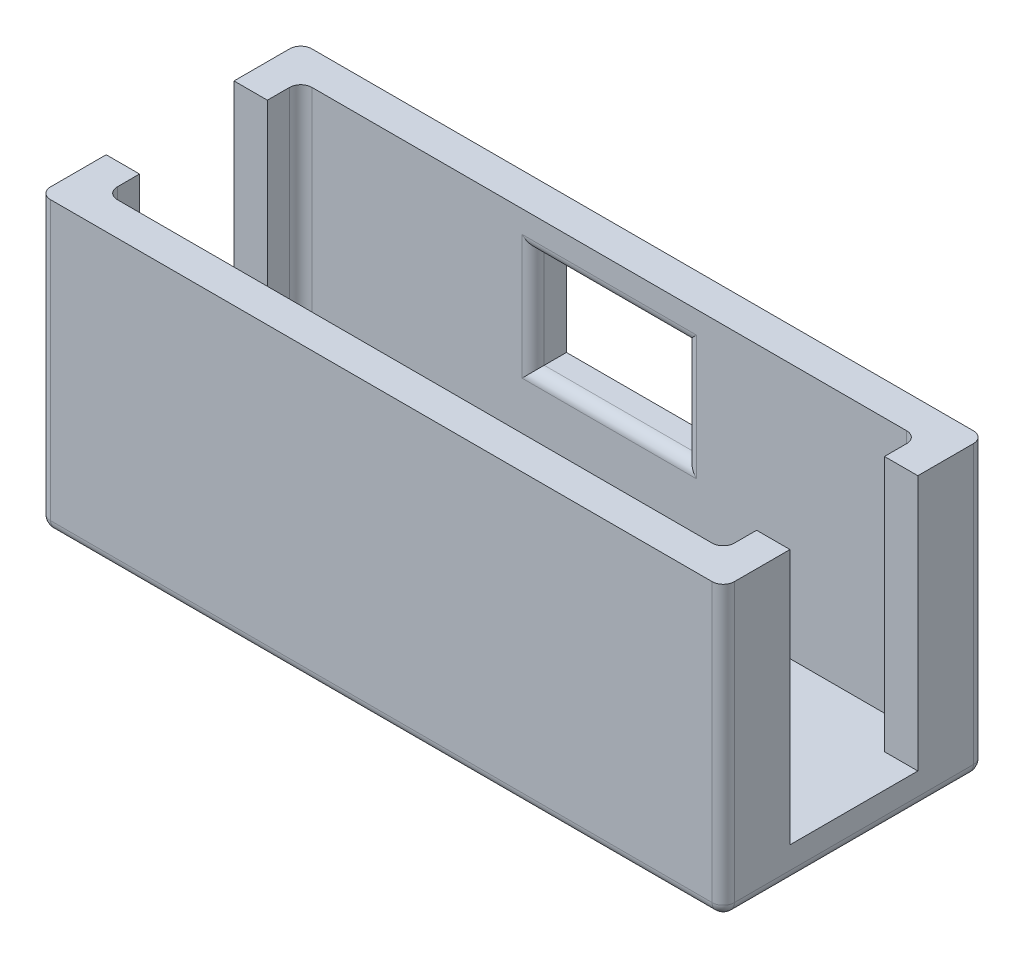
SolidWorks part; units mm, degrees
ref_plane "Front Plane" through (0, 0, 0) normal (0, 0, 1) x (1, 0, 0)
ref_plane "Top Plane" through (0, 0, 0) normal (0, 1, 0) x (1, 0, 0)
ref_plane "Right Plane" through (0, 0, 0) normal (1, 0, 0) x (0, 0, -1)
sketch "Sketch1" plane through (0, 0, 0) normal (0, 1, 0) x (1, 0, 0)
  line L0 (-33.75, -14.75) -> (-33.75, 14.75)
  line L1 (-30.75, -11.75) -> (30.75, -11.75)
  line L2 (-30.75, -11.75) -> (-30.75, 11.75)
  line L3 (-30.75, 11.75) -> (30.75, 11.75)
  line L4 (30.75, -11.75) -> (30.75, 11.75)
  line L5 (-30.75, -11.75) -> (30.75, 11.75) construction
  line L6 (-30.75, 11.75) -> (30.75, -11.75) construction
  line L7 (-33.75, 14.75) -> (33.75, 14.75)
  line L8 (33.75, -14.75) -> (33.75, 14.75)
  line L9 (-33.75, -14.75) -> (33.75, -14.75)
  point P0 (0, 0)
  dimension "D1" = 61.5
  dimension "D2" = 23.5
  dimension "D3" = 3
extrude "Boss-Extrude1" add sketch "Sketch1" along normal blind 3 contours L2 L1 L4 L3
sketch "Sketch2" plane through (0, 3, 0) normal (0, 1, 0) x (1, 0, 0)
  line L0 (-30.75, -5.75) -> (-27.75, -5.75)
  line L1 (-30.75, -11.75) -> (-30.75, 11.75) construction
  line L2 (-27.75, -5.75) -> (-27.75, -8.75)
  line L3 (-27.75, -8.75) -> (27.75, -8.75)
  line L4 (0, -1.65) -> (0, 1.65) construction
  line L5 (0, -8.75) -> (0, -11.75)
  line L6 (30.75, -11.75) -> (-30.75, -11.75)
  line L7 (-30.75, -11.75) -> (-30.75, -5.75)
  line L8 (0, 0) -> (-3.5361, 0)
  line L9 (-1.65, 0) -> (1.65, 0) construction
  line L10 (30.75, 11.75) -> (-30.75, 11.75)
  line L11 (0, 8.75) -> (0, 11.75)
  line L12 (-27.75, 8.75) -> (27.75, 8.75)
  line L13 (-27.75, 5.75) -> (-27.75, 8.75)
  line L14 (-30.75, 5.75) -> (-27.75, 5.75)
  line L15 (-30.75, 11.75) -> (-30.75, 5.75)
  line L16 (27.75, 5.75) -> (27.75, 8.75)
  line L17 (30.75, 5.75) -> (27.75, 5.75)
  line L18 (30.75, 11.75) -> (30.75, 5.75)
  line L19 (27.75, -5.75) -> (27.75, -8.75)
  line L20 (30.75, -5.75) -> (27.75, -5.75)
  line L21 (30.75, -11.75) -> (30.75, -5.75)
  line M15 (-30.75, 11.75) -> (-30.75, -11.75)
  line M16 (-30.75, -11.75) -> (30.75, -11.75)
  line M17 (30.75, -11.75) -> (30.75, 11.75)
  dimension "D1" = 3
  dimension "D2" = 3
  dimension "D3" = 3
extrude "Boss-Extrude2" add sketch "Sketch2" along normal blind 23 contours L14 L13 L12 L11 L10 M15 | L5 L3 L2 L0 M15 M16 | L20 L19 L3 L5 M17 M16
fillet "Fillet1" radius 1 12 edges at (-30.75, 0, 0) (0, 0, 11.75) (30.75, 0, 0) (0, 0, -11.75) (27.75, 14.5, -8.75) (27.75, 14.5, 8.75) (-27.75, 14.5, 8.75) (-27.75, 14.5, -8.75) (-30.75, 13, -11.75) (30.75, 13, -11.75) (30.75, 13, 11.75) (-30.75, 13, 11.75)
sketch "Sketch3" plane through (0, 0, -11.75) normal (0, 0, -1) x (-1, 0, 0)
  line L0 (0, 26) -> (0, 23)
  line L1 (-29.75, 26) -> (29.75, 26) construction
  line L2 (0, 12.925) -> (0, -12.925) construction
  line L3 (0, 23) -> (-6.85, 23)
  line L4 (-6.85, 23) -> (-6.85, 13.8)
  line L5 (-6.85, 13.8) -> (6.85, 13.8)
  line L6 (6.85, 13.8) -> (6.85, 23)
  line L7 (6.85, 23) -> (0, 23)
  dimension "D1" = 9.2
  dimension "D2" = 3
  dimension "D3" = 13.7
  dimension "D4" = 6.85
extrude "Cut-Extrude1" cut sketch "Sketch3" against normal up to next contours L6 L7 L3 L4 L5
fillet "Fillet2" radius 1 4 edges at (0, 23, -8.75) (0, 13.8, -8.75) (6.85, 18.4, -8.75) (-6.85, 18.4, -8.75)
